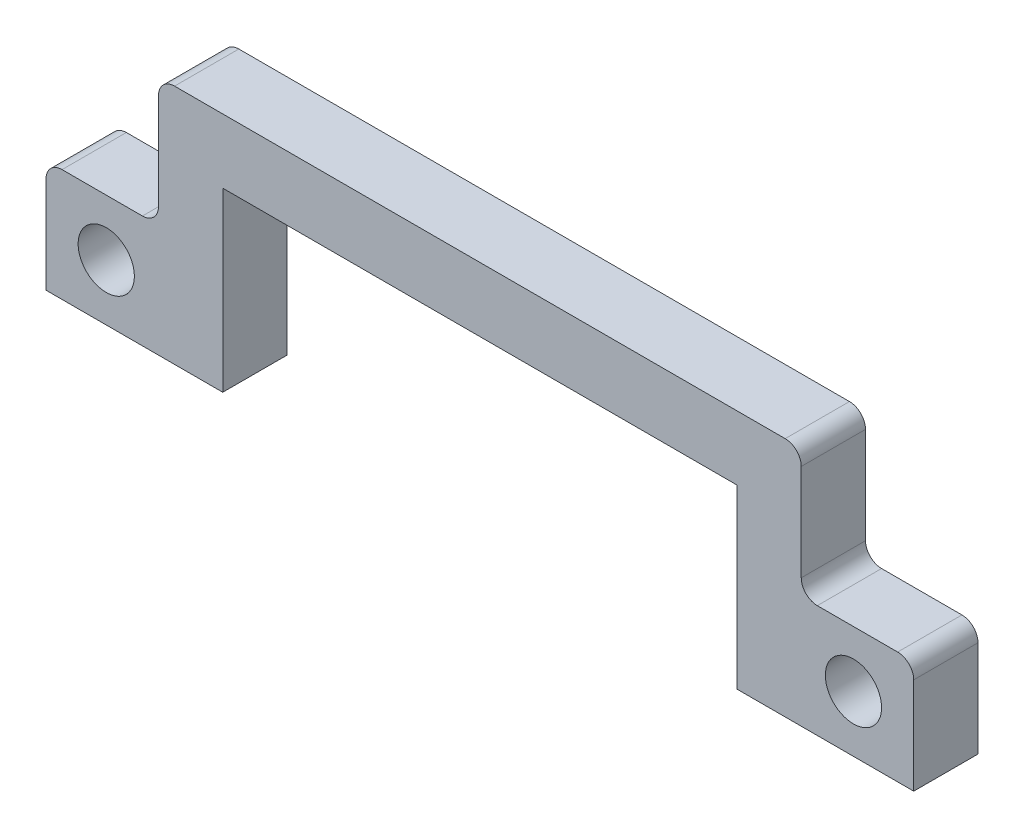
SolidWorks part; units mm, degrees
ref_plane "Front Plane" through (0, 0, 0) normal (0, 0, 1) x (1, 0, 0)
ref_plane "Top Plane" through (0, 0, 0) normal (0, 1, 0) x (1, 0, 0)
ref_plane "Right Plane" through (0, 0, 0) normal (1, 0, 0) x (0, 0, -1)
sketch "Sketch1" plane through (0, 0, 0) normal (0, 0, 1) x (1, 0, 0)
  line L0 (-27, -11) -> (-16, -11)
  line L1 (-16, -11) -> (-16, 0)
  line L2 (-16, 0) -> (16, 0)
  line L3 (16, 0) -> (16, -11)
  line L4 (16, -11) -> (27, -11)
  line L5 (27, -11) -> (27, -4)
  line L6 (27, -4) -> (20, -4)
  line L7 (20, -4) -> (20, 4)
  line L8 (20, 4) -> (-20, 4)
  line L9 (-20, 4) -> (-20, -4)
  line L10 (-20, -4) -> (-27, -4)
  line L11 (-27, -4) -> (-27, -11)
  point P2 (0, 0)
  point P13 (0, 4)
  dimension "D1" = 32
  dimension "D2" = 11
  dimension "D3" = 7
  dimension "D4" = 4
  dimension "D5" = 4
  dimension "D6" = 11
extrude "Boss-Extrude1" add sketch "Sketch1" along normal blind 4
sketch "Sketch2" plane through (0, 0, 4) normal (0, 0, 1) x (1, 0, 0)
  line L0 (-27, -4) -> (-27, -11) construction
  circle A0 centre (-23.25, -7.5) radius 1.75
  point P5 (-27, -7.5)
  dimension "D1" = 3.5
  dimension "D2" = 3.75
extrude "Cut-Extrude1" cut sketch "Sketch2" against normal blind 4
mirror "Mirror1" about plane through (0, 0, 0) normal (1, 0, 0) of "Cut-Extrude1"
fillet "Fillet1" radius 1 6 edges at (27, -4, 2) (20, -4, 2) (20, 4, 2) (-27, -4, 2) (-20, -4, 2) (-20, 4, 2)
